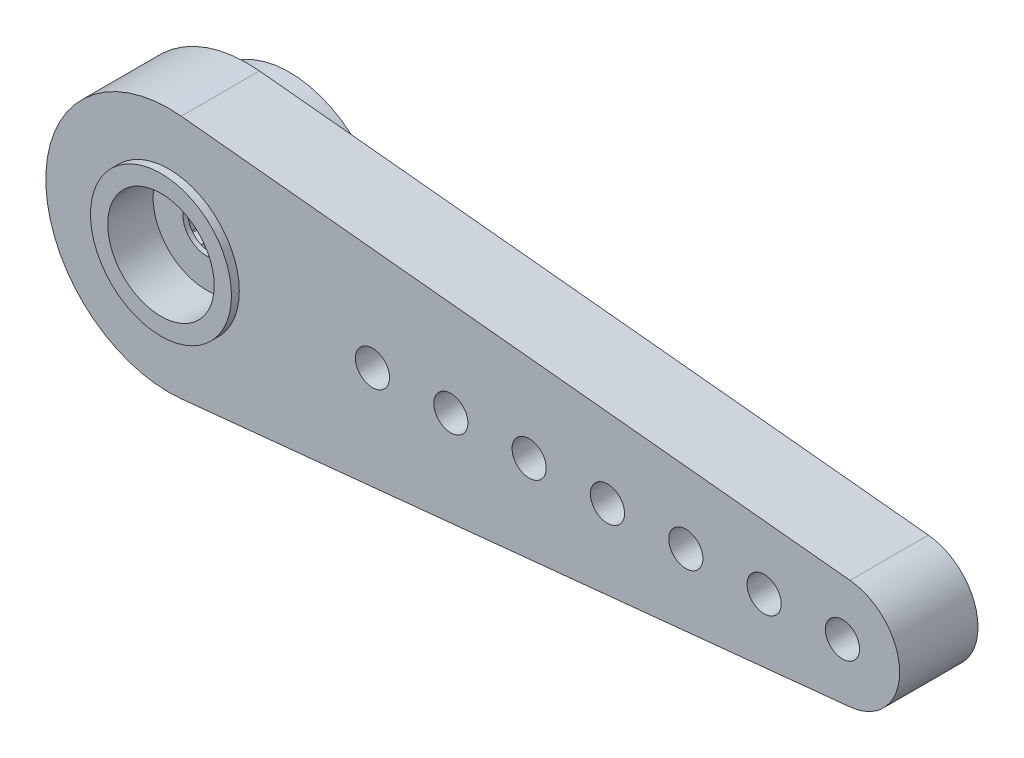
SolidWorks part; units mm, degrees
material "Nylon 101"
ref_plane "Front Plane" through (0, 0, 0) normal (0, 0, 1) x (1, 0, 0)
ref_plane "Top Plane" through (0, 0, 0) normal (0, 1, 0) x (1, 0, 0)
ref_plane "Right Plane" through (0, 0, 0) normal (1, 0, 0) x (0, 0, -1)
sketch "Sketch1" plane through (0, 0, 0) normal (0, 0, 1) x (1, 0, 0)
  line L0 (0.7885, 7.8103) -> (43.4855, 3.5)
  line L1 (43.4855, -3.5) -> (0.7885, -7.8103)
  line L2 (0, 0) -> (43.1322, 0) construction
  line L3 (0, 7.85) -> (0, -7.85) construction
  line L4 (-7.85, 0) -> (0, 0) construction
  line L5 (43.1322, 0) -> (46.65, 0) construction
  arc A0 (0.7885, 7.8103) -> (0.7885, -7.8103) centre (0, 0) ccw
  arc A1 (43.4855, -3.5) -> (43.4855, 3.5) centre (43.1322, 0) ccw
  point P10 (42.4378, 4.1967)
  dimension "D1" = 15.7
  dimension "D2" = 54.5
  dimension "D3" = 7
extrude "Boss-Extrude1" add sketch "Sketch1" along normal blind 5
sketch "Sketch2" plane through (0, 0, 5) normal (0, 0, 1) x (1, 0, 0)
  circle A0 centre (0, 0) radius 1.5
  dimension "D1" = 3
extrude "Cut-Extrude1" cut sketch "Sketch2" against normal up to next
sketch "Sketch3" plane through (0, 0, 5) normal (0, 0, 1) x (1, 0, 0)
  circle A0 centre (0, 0) radius 3.4
  dimension "D1" = 6.8
extrude "Cut-Extrude2" cut sketch "Sketch3" against normal blind 2.4
sketch "Sketch4" plane through (0, 0, 5) normal (0, 0, 1) x (1, 0, 0)
  circle A0 centre (0, 0) radius 3.4 construction
  circle A1 centre (0, 0) radius 3.4
  circle A2 centre (0, 0) radius 4.5
  dimension "D1" = 9
extrude "Boss-Extrude2" add sketch "Sketch4" along normal blind 0.5
sketch "Sketch6" plane through (0, 0, 0) normal (0, 0, -1) x (-1, 0, 0)
  circle A0 centre (0, 0) radius 6
  circle A1 centre (0, 0) radius 1.5 construction
  circle A2 centre (0, 0) radius 1.5
  dimension "D1" = 12
extrude "Boss-Extrude3" add sketch "Sketch6" along normal blind 2.7
sketch "Sketch7" plane through (0, 0, -2.7) normal (0, 0, -1) x (-1, 0, 0)
  circle A0 centre (0, 0) radius 3.75
  dimension "D1" = 7.5
extrude "Cut-Extrude4" cut sketch "Sketch7" against normal blind 5
sketch "Sketch8" plane through (0, 0, -2.7) normal (0, 0, -1) x (-1, 0, 0)
  line L0 (-0.7387, 3.6765) -> (0, 3.25)
  line L1 (0, 3.25) -> (0.7387, 3.6765)
  circle A0 centre (0, 0) radius 3.75 construction
  circle A1 centre (0, 0) radius 3.75 construction
  arc A2 (0.7387, 3.6765) -> (-0.7387, 3.6765) centre (0, 0) ccw
  circle A3 centre (0, 0) radius 3.25 construction
  dimension "D1" = 6.5
  dimension "D2" = 120
extrude "Boss-Extrude4" add sketch "Sketch8" against normal up to surface (5 mm away) up to face at (-3.75, 0, 2.3)
pattern_circular "CirPattern2" count 15 over 360 about axis through (0, 0, 0) along (0, 0, 1) of "Boss-Extrude4"
sketch "Sketch10" plane through (0, 0, 5) normal (0, 0, 1) x (1, 0, 0)
  line L0 (13, 0) -> (18, 0) construction
  line L1 (18, 0) -> (23, 0) construction
  line L2 (23, 0) -> (28, 0) construction
  line L3 (28, 0) -> (33, 0) construction
  line L4 (33, 0) -> (38, 0) construction
  line L5 (38, 0) -> (43, 0) construction
  line L6 (0, 0) -> (13, 0) construction
  circle A0 centre (43, 0) radius 1.09
  circle A1 centre (38, 0) radius 1.09
  circle A2 centre (33, 0) radius 1.09
  circle A3 centre (28, 0) radius 1.09
  circle A5 centre (23, 0) radius 1.09
  circle A6 centre (18, 0) radius 1.09
  circle A7 centre (13, 0) radius 1.09
  dimension "D1" = 2.18
  dimension "D2" = 5
  dimension "D3" = 13
extrude "Cut-Extrude5" cut sketch "Sketch10" against normal up to next
